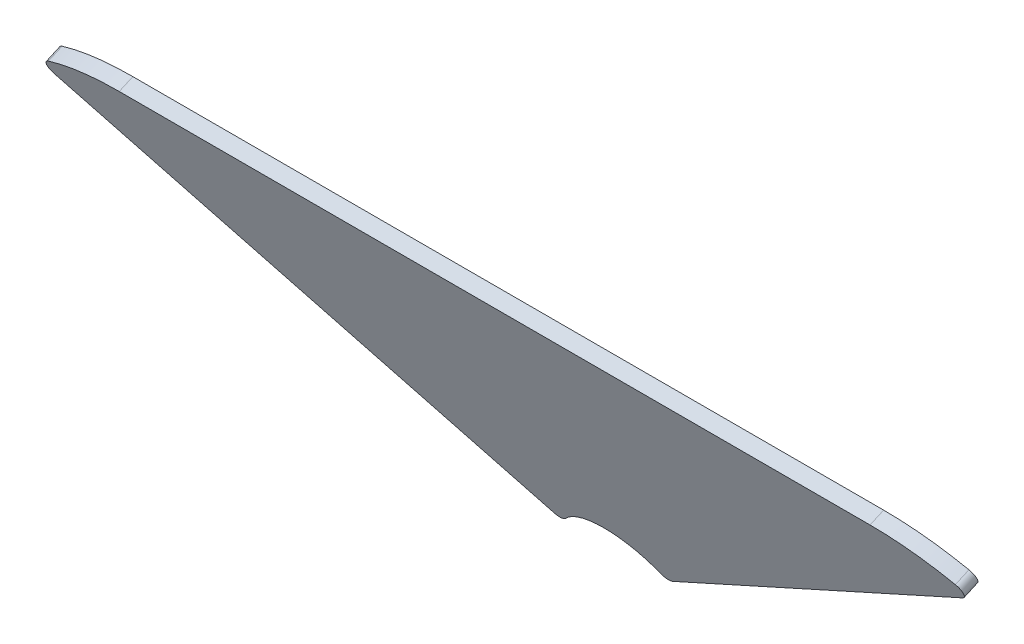
SolidWorks part; units mm, degrees
ref_plane "Front Plane" through (0, 0, 0) normal (0, 0, 1) x (1, 0, 0)
ref_plane "Top Plane" through (0, 0, 0) normal (0, 1, 0) x (1, 0, 0)
ref_plane "Right Plane" through (0, 0, 0) normal (1, 0, 0) x (0, 0, -1)
sketch "Sketch2" plane through (837.1765, 0, 0) normal (1, 0, 0) x (0, 0, -1)
  line L0 (-1722.9912, 961.5315) -> (-1717.1925, 964.1196)
  line L1 (-1717.1925, 964.1196) -> (-1664.5115, 846.0878)
  circle A1 centre (-1734.5884, 956.3553) radius 12.7 construction
  spline S3 degree 3 poles (-1672.5958, 849.9723) (-1673.5477, 849.8952) (-1674.1749, 849.8046) (-1675.1056, 849.6161) (-1675.4141, 849.5444) (-1676.0278, 849.383) (-1676.3323, 849.2934) (-1677.2211, 849.0032) (-1677.7876, 848.7801) (-1678.6002, 848.3983) (-1678.8658, 848.2625) (-1679.3759, 847.9783) (-1679.6212, 847.8297) (-1680.3284, 847.3632) (-1680.7621, 847.0248) (-1681.5498, 846.2807) (-1681.8942, 845.8836) (-1682.4751, 845.0381) (-1682.7133, 844.5881) (-1683.068, 843.6224) (-1683.1776, 843.1254) (-1683.239, 842.3556) (-1683.2421, 842.095) (-1683.212, 841.5648) (-1683.1783, 841.294) (-1683.024, 840.491) (-1682.8511, 839.9617) (-1682.4897, 839.1774) (-1682.3514, 838.9169) (-1682.0477, 838.4116) (-1681.8818, 838.1655) (-1681.523, 837.6858) (-1681.3302, 837.4523) (-1680.9182, 836.9982) (-1680.6991, 836.7779) (-1680.0161, 836.1492) (-1679.5231, 835.7681) (-1678.7294, 835.2541) (-1678.4548, 835.0921) (-1677.8968, 834.7935) (-1677.6124, 834.6562) (-1676.7433, 834.2805) (-1676.1429, 834.0779) (-1674.8968, 833.7796) (-1674.2664, 833.6881) (-1673.0044, 833.6277) (-1672.3691, 833.6585) (-1671.0981, 833.8585) (-1670.4856, 834.024) (-1669.6006, 834.3689) (-1669.3112, 834.5) (-1668.7442, 834.7954) (-1668.4663, 834.9601) (-1667.6711, 835.4907) (-1667.1844, 835.8964) (-1666.5163, 836.577) (-1666.3034, 836.8169) (-1665.9068, 837.3099) (-1665.722, 837.564) (-1665.3779, 838.0864) (-1665.2187, 838.3547) (-1664.9255, 838.9046) (-1664.791, 839.1879) (-1664.432, 840.0421) (-1664.2502, 840.6186) (-1663.9965, 841.7808) (-1663.9255, 842.3714) (-1663.9008, 843.5079) (-1663.945, 844.0593) (-1664.0977, 844.8597) (-1664.1634, 845.1221) (-1664.3209, 845.6257) (-1664.413, 845.8686) (-1664.6235, 846.3369) (-1664.7419, 846.5625) (-1665.0057, 846.9964) (-1665.1519, 847.2059) (-1665.6245, 847.798) (-1665.9841, 848.1462) (-1666.7949, 848.758) (-1667.2503, 849.0223) (-1668.2222, 849.4504) (-1668.7421, 849.6177) (-1669.5789, 849.8031) (-1669.8673, 849.8536) (-1670.4504, 849.9311) (-1670.7467, 849.9585) (-1671.3491, 849.9916) (-1671.6553, 849.9974) (-1672.278, 849.9878) (-1672.5958, 849.9723) (-1673.5477, 849.8952) (-1674.1749, 849.8046) knots -0.015625 -0.015625 0 0 0.03125 0.03125 0.046875 0.046875 0.0625 0.0625 0.09375 0.09375 0.109375 0.109375 0.125 0.125 0.15625 0.15625 0.1875 0.1875 0.21875 0.21875 0.25 0.25 0.265625 0.265625 0.28125 0.28125 0.3125 0.3125 0.328125 0.328125 0.34375 0.34375 0.359375 0.359375 0.375 0.375 0.40625 0.40625 0.421875 0.421875 0.4375 0.4375 0.46875 0.46875 0.5 0.5 0.53125 0.53125 0.5625 0.5625 0.578125 0.578125 0.59375 0.59375 0.625 0.625 0.640625 0.640625 0.65625 0.65625 0.671875 0.671875 0.6875 0.6875 0.71875 0.71875 0.75 0.75 0.78125 0.78125 0.796875 0.796875 0.8125 0.8125 0.828125 0.828125 0.84375 0.84375 0.875 0.875 0.90625 0.90625 0.9375 0.9375 0.953125 0.953125 0.96875 0.96875 0.984375 0.984375 1 1 1.03125 1.03125 1.046875 only from (-1672.9131, 849.9466) to (-1672.9131, 849.9466) construction
  point P4 (-1734.5884, 956.3553)
  dimension "D1" = 6.35
ref_plane "Plane1" through (837.1765, 964.1196, 1717.1925) normal (0, 0.4076, -0.9132) x (-1, 0, 0)
sketch "Sketch3" plane through (837.1765, 964.1196, 1717.1925) normal (0, 0.4076, -0.9132) x (-1, 0, 0)
  line L0 (200.465, -319.1426) -> (364.1746, -212.1254)
  line L1 (200.465, -319.1426) -> (364.1746, -212.1254) construction
  line L2 (348.2988, -210.3187) -> (28.1004, -210.3187)
  line L3 (348.2988, -210.3187) -> (28.1004, -210.3187) construction
  line L4 (12.2244, -212.1253) -> (175.9323, -319.1412)
  line L5 (12.2244, -212.1253) -> (175.9323, -319.1412) construction
  line L6 (166.1468, -335.4914) -> (166.1318, -335.493)
  line L7 (166.1468, -335.4914) -> (166.1318, -335.493) construction
  line L8 (166.1318, -335.493) -> (-9.0348, -220.9873)
  line L9 (166.1318, -335.493) -> (-9.0348, -220.9873) construction
  line L10 (28.1004, -184.9187) -> (348.2988, -184.9187)
  line L11 (28.1004, -184.9187) -> (348.2988, -184.9187) construction
  line L12 (385.4341, -220.9873) -> (210.2675, -335.493)
  line L13 (385.4341, -220.9873) -> (210.2675, -335.493) construction
  line L14 (210.2675, -335.493) -> (210.2565, -335.4943)
  line L15 (210.2675, -335.493) -> (210.2565, -335.4943) construction
  line L16 (-9.0348, -220.9873) -> (12.2244, -212.1253) construction
  line L17 (28.1004, -184.9187) -> (28.1004, -210.3187) construction
  line L18 (348.2988, -184.9187) -> (348.2988, -210.3187) construction
  line L19 (177.1127, -118.42) -> (187.5358, -134.3648) construction
  line L20 (143.0858, -118.42) -> (132.6627, -134.3648) construction
  line L21 (364.1746, -212.1254) -> (385.4341, -220.9873) construction
  line L22 (175.9323, -319.1412) -> (200.465, -319.1426) construction
  line L23 (137.8743, -126.3924) -> (-26.5056, -18.9376)
  line L24 (-26.5056, -18.9376) -> (-39.0764, -10.7201)
  line L25 (-39.0764, -10.7201) -> (-51.6473, -2.5025) construction
  line L26 (182.3243, -126.3924) -> (346.7039, -18.9376)
  line L27 (346.7039, -18.9376) -> (359.2746, -10.7202)
  line L28 (359.2746, -10.7202) -> (371.8453, -2.5027) construction
  line L29 (320.1984, 0) -> (0, 0)
  arc A1 (0, 0) -> (-39.0764, -10.7201) centre (0, -76.5802) ccw
  arc A2 (320.1984, 0) -> (359.2746, -10.7202) centre (320.1984, -76.5785) cw
  arc A3 (182.3243, -126.3924) -> (137.8743, -126.3924) centre (160.0993, -140.9209) ccw
  spline S0 degree 3 poles (659.9519, 743.1282) (428.1653, -254.3173) (397.4834, -218.3344) (360.2524, -211.3258) (358.2751, -211.0142) (356.2894, -210.7599) (354.2973, -210.5624) (352.3004, -210.422) (350.6337, -210.3538) (315.7098, -209.6595) (281.1145, -227.6118) (267.7262, 786.4165) knots -6.722567 -6.722567 -6.722567 -6.722567 0.125 0.25 0.375 0.5 0.625 0.75 0.875 0.9375 7.29437 7.29437 7.29437 7.29437 only from (364.1746, -212.1254) to (348.2988, -210.3187)
  spline S1 degree 3 poles (364.1746, -212.1254) (363.5233, -211.9804) (362.2195, -211.6961) (360.2524, -211.3258) (358.2751, -211.0142) (356.2894, -210.7599) (354.2973, -210.5624) (352.3004, -210.422) (350.6337, -210.3538) (349.2996, -210.3272) (348.6324, -210.3211) (348.2988, -210.3187) knots 0 0 0 0 0.125 0.25 0.375 0.5 0.625 0.75 0.875 0.9375 1 1 1 1 construction
  spline S2 degree 3 poles (97.7861, 787.2485) (97.2182, -236.2705) (60.6222, -208.9011) (24.0988, -210.4229) (22.1019, -210.5631) (20.1097, -210.7605) (18.1241, -211.0144) (16.4762, -211.2736) (15.1629, -211.5099) (14.1806, -211.7016) (13.3646, -211.8735) (-18.1256, -218.7856) (-47.5419, -233.8893) (-286.4808, 742.2125) knots -6.472941 -6.472941 -6.472941 -6.472941 0.125 0.25 0.375 0.5 0.625 0.75 0.8125 0.875 0.9375 0.96875 6.915062 6.915062 6.915062 6.915062 only from (28.1004, -210.3187) to (12.2244, -212.1253)
  spline S3 degree 3 poles (28.1004, -210.3187) (27.4332, -210.3239) (26.0988, -210.3395) (24.0988, -210.4229) (22.1019, -210.5631) (20.1097, -210.7605) (18.1241, -211.0144) (16.4762, -211.2736) (15.1629, -211.5099) (14.1806, -211.7016) (13.3646, -211.8735) (12.7129, -212.0165) (12.3872, -212.089) (12.2244, -212.1253) knots 0 0 0 0 0.125 0.25 0.375 0.5 0.625 0.75 0.8125 0.875 0.9375 0.96875 1 1 1 1 construction
  spline S4 degree 3 poles (982.7808, 271.6051) (158.1545, -326.467) (174.5052, -317.3606) (176.0525, -319.2694) (176.089, -319.3623) (176.1027, -319.4622) (176.1033, -319.564) (176.0581, -319.8426) (175.748, -320.4402) (175.1304, -321.2349) (174.4623, -322.0037) (173.9265, -322.6112) (172.5796, -324.1234) (170.345, -326.7511) (168.4081, -329.8622) (167.3716, -332.0603) (166.987, -332.9968) (166.7089, -333.7572) (166.5162, -334.3334) (166.3648, -334.8169) (165.1032, -339.4892) (157.37, -341.2292) (-739.9858, 87.4471) knots -0.369024 -0.369024 -0.369024 -0.369024 0.003906 0.007812 0.015625 0.019531 0.023438 0.03125 0.0625 0.125 0.1875 0.21875 0.25 0.5 0.75 0.8125 0.875 0.90625 0.9375 0.96875 0.984375 1.679663 1.679663 1.679663 1.679663 only from (175.9323, -319.1412) to (166.1468, -335.4914)
  spline S5 degree 3 poles (175.9323, -319.1412) (175.9519, -319.1578) (175.9897, -319.1918) (176.0525, -319.2694) (176.089, -319.3623) (176.1027, -319.4622) (176.1033, -319.564) (176.0581, -319.8426) (175.748, -320.4402) (175.1304, -321.2349) (174.4623, -322.0037) (173.9265, -322.6112) (172.5796, -324.1234) (170.345, -326.7511) (168.4081, -329.8622) (167.3716, -332.0603) (166.987, -332.9968) (166.7089, -333.7572) (166.5162, -334.3334) (166.3648, -334.8169) (166.2586, -335.2104) (166.1929, -335.4018) (166.1468, -335.4914) knots 0 0 0 0 0.003906 0.007812 0.015625 0.019531 0.023438 0.03125 0.0625 0.125 0.1875 0.21875 0.25 0.5 0.75 0.8125 0.875 0.90625 0.9375 0.96875 0.984375 1 1 1 1 construction
  spline S6 degree 3 poles (-493.6996, 653.7081) (83.9817, -212.3541) (22.0311, -198.2847) (-13.0482, -223.7444) (-14.3371, -224.7316) (-15.601, -225.7507) (-17.2514, -227.1514) (-19.2467, -228.98) (-21.5249, -231.2949) (-24.3974, -234.5355) (-27.66, -238.8621) (-30.436, -243.5165) (-32.339, -247.4067) (-33.6013, -250.3996) (-34.6934, -253.4586) (-35.4578, -256.0552) (-35.9789, -258.1561) (-36.3229, -259.7426) (-42.747, -294.5132) (-19.81, -333.8714) (-1033.9267, -186.5236) knots -2.378042 -2.378042 -2.378042 -2.378042 0.0625 0.09375 0.125 0.15625 0.1875 0.25 0.3125 0.375 0.5 0.625 0.6875 0.75 0.8125 0.875 0.90625 0.9375 0.96875 2.948348 2.948348 2.948348 2.948348 only from (-9.0348, -220.9873) to (-36.8675, -262.943)
  spline S7 degree 3 poles (-9.0348, -220.9873) (-9.9432, -221.5758) (-11.2964, -222.473) (-13.0482, -223.7444) (-14.3371, -224.7316) (-15.601, -225.7507) (-17.2514, -227.1514) (-19.2467, -228.98) (-21.5249, -231.2949) (-24.3974, -234.5355) (-27.66, -238.8621) (-30.436, -243.5165) (-32.339, -247.4067) (-33.6013, -250.3996) (-34.6934, -253.4586) (-35.4578, -256.0552) (-35.9789, -258.1561) (-36.3229, -259.7426) (-36.6178, -261.3389) (-36.7862, -262.408) (-36.8675, -262.943) knots 0 0 0 0 0.0625 0.09375 0.125 0.15625 0.1875 0.25 0.3125 0.375 0.5 0.625 0.6875 0.75 0.8125 0.875 0.90625 0.9375 0.96875 1 1 1 1 construction
  spline S8 degree 3 poles (-47.8786, -256.9695) (-36.9078, -258.8257) (-2.6541, -272.3181) (-50.068, -265.5733) (-97.5183, -258.8233) (-60.8226, -255.4226) (-49.7712, -256.7002) knots -1.046927 -1.046927 -1.046927 -1.046927 0.5 0.5 0.5 2.047388 2.047388 2.047388 2.047388 weights 4.840134 1.66871 0.388666 1 0.388483 1.669474 4.842974 only from (-36.8675, -262.943) to (-62.0131, -259.366)
  spline S9 degree 3 poles (-36.8675, -262.943) (-37.1611, -265.5366) (-42.6448, -266.6293) (-50.068, -265.5733) (-57.4912, -264.5173) (-62.4534, -261.9387) (-62.0131, -259.366) knots 0 0 0 0 0.5 0.5 0.5 1 1 1 1 weights 1 0.802404 0.802404 1 0.802404 0.802404 1 construction
  spline S10 degree 3 poles (-1060.3982, -202.94) (-56.4438, -329.2134) (-67.2811, -292.1623) (-61.6548, -257.0711) (-61.3619, -255.4381) (-60.9617, -253.4879) (-60.0654, -249.6084) (-57.6106, -241.3303) (-49.7965, -224.3685) (-35.6466, -208.0634) (-17.9273, -196.2171) (-5.752, -190.8135) (4.4288, -187.7666) (12.2284, -186.1252) (18.8192, -185.3063) (73.9472, -181.7994) (128.2452, -228.2224) (116.8317, 811.1153) knots -0.805545 -0.805545 -0.805545 -0.805545 0.007812 0.015625 0.03125 0.046875 0.0625 0.125 0.25 0.5 0.625 0.75 0.8125 0.875 0.9375 0.96875 2.175289 2.175289 2.175289 2.175289 only from (-62.0131, -259.366) to (28.1004, -184.9187)
  spline S11 degree 3 poles (-62.0131, -259.366) (-61.9641, -259.0378) (-61.865, -258.3816) (-61.6548, -257.0711) (-61.3619, -255.4381) (-60.9617, -253.4879) (-60.0654, -249.6084) (-57.6106, -241.3303) (-49.7965, -224.3685) (-35.6466, -208.0634) (-17.9273, -196.2171) (-5.752, -190.8135) (4.4288, -187.7666) (12.2284, -186.1252) (18.8192, -185.3063) (24.1188, -184.9692) (26.7732, -184.9275) (28.1004, -184.9187) knots 0 0 0 0 0.007812 0.015625 0.03125 0.046875 0.0625 0.125 0.25 0.5 0.625 0.75 0.8125 0.875 0.9375 0.96875 1 1 1 1 construction
  spline S12 degree 3 poles (929.1577, -998.9148) (26.9808, -381.5261) (268.5777, -127.2907) (408.505, -203.9885) (426.1982, -224.3663) (434.0103, -241.3309) (436.4648, -249.6066) (437.3606, -253.4879) (437.7608, -255.4383) (438.0537, -257.0712) (443.7072, -292.3117) (433.0852, -329.5148) (1436.622, -201.5799) knots -2.951338 -2.951338 -2.951338 -2.951338 0.25 0.5 0.75 0.875 0.9375 0.953125 0.96875 0.984375 0.992188 1.809139 1.809139 1.809139 1.809139 only from (348.2988, -184.9187) to (438.4123, -259.366)
  spline S13 degree 3 poles (348.2988, -184.9187) (358.9172, -184.9233) (380.1516, -188.4473) (408.505, -203.9885) (426.1982, -224.3663) (434.0103, -241.3309) (436.4648, -249.6066) (437.3606, -253.4879) (437.7608, -255.4383) (438.0537, -257.0712) (438.2639, -258.3817) (438.3632, -259.0378) (438.4123, -259.366) knots 0 0 0 0 0.25 0.5 0.75 0.875 0.9375 0.953125 0.96875 0.984375 0.992188 1 1 1 1 construction
  spline S14 degree 3 poles (429.3298, -256.4787) (440.8837, -256.216) (453.9089, -261.6696) (426.4673, -265.5733) (399.0344, -269.4757) (410.0144, -260.6083) (421.1832, -257.6379) knots -0.70583 -0.70583 -0.70583 -0.70583 0.5 0.5 0.5 1.705627 1.705627 1.705627 1.705627 weights 3.01812 1.196171 0.523464 1 0.523545 1.195944 3.017197 only from (438.4123, -259.366) to (413.2667, -262.943)
  spline S15 degree 3 poles (438.4123, -259.366) (438.8526, -261.9387) (433.8904, -264.5173) (426.4673, -265.5733) (419.0441, -266.6293) (413.5604, -265.5366) (413.2667, -262.943) knots 0 0 0 0 0.5 0.5 0.5 1 1 1 1 weights 1 0.802404 0.802404 1 0.802404 0.802404 1 construction
  spline S16 degree 3 poles (1410.455, -188.0131) (395.1635, -336.6809) (419.3711, -295.7703) (412.6239, -259.2105) (412.0098, -256.5745) (411.092, -253.4587) (408.9087, -247.34) (405.3648, -240.5921) (400.144, -233.6703) (396.4438, -229.712) (393.2517, -226.7855) (390.7497, -224.7145) (353.7782, -197.1496) (288.4588, -212.0584) (872.3304, 652.4537) knots -2.022142 -2.022142 -2.022142 -2.022142 0.03125 0.0625 0.125 0.1875 0.25 0.5 0.625 0.75 0.8125 0.875 0.9375 3.474833 3.474833 3.474833 3.474833 only from (413.2667, -262.943) to (385.4341, -220.9873)
  spline S17 degree 3 poles (413.2667, -262.943) (413.1855, -262.408) (413.0167, -261.3389) (412.6239, -259.2105) (412.0098, -256.5745) (411.092, -253.4587) (408.9087, -247.34) (405.3648, -240.5921) (400.144, -233.6703) (396.4438, -229.712) (393.2517, -226.7855) (390.7497, -224.7145) (388.146, -222.7732) (386.3426, -221.5756) (385.4341, -220.9873) knots 0 0 0 0 0.03125 0.0625 0.125 0.1875 0.25 0.5 0.625 0.75 0.8125 0.875 0.9375 1 1 1 1 construction
  spline S18 degree 3 poles (1000.6787, 277.0647) (258.2318, -323.4154) (211.9671, -341.0766) (210.1437, -335.2146) (210.0999, -335.0684) (210.0561, -334.9224) (209.9827, -334.6795) (209.8633, -334.292) (209.6891, -333.7631) (209.4829, -333.1919) (209.261, -332.6267) (208.945, -331.8812) (208.3413, -330.5985) (207.5457, -329.1845) (206.6638, -327.8234) (205.9639, -326.8282) (205.2304, -325.857) (204.4683, -324.9081) (203.8136, -324.1339) (203.2815, -323.5219) (202.745, -322.9138) (202.2044, -322.3095) (201.6701, -321.6994) (201.3429, -321.3124) (201.0889, -320.9963) (200.9039, -320.7549) (200.7268, -320.5075) (200.5614, -320.2517) (200.4403, -320.0277) (200.3608, -319.8391) (200.3156, -319.6924) (200.2921, -319.5407) (200.2998, -319.414) (200.3287, -319.3195) (200.363, -319.254) (201.9646, -317.2491) (217.5274, -324.4122) (-635.2893, 229.8776) knots -0.918902 -0.918902 -0.918902 -0.918902 0.007812 0.015625 0.023438 0.03125 0.039062 0.0625 0.09375 0.125 0.15625 0.1875 0.25 0.375 0.4375 0.5 0.5625 0.625 0.6875 0.71875 0.75 0.8125 0.84375 0.875 0.890625 0.90625 0.921875 0.9375 0.953125 0.960938 0.96875 0.976562 0.984375 0.988281 0.992188 0.996094 1.390011 1.390011 1.390011 1.390011 only from (210.2565, -335.4943) to (200.465, -319.1426)
  spline S19 degree 3 poles (210.2565, -335.4943) (210.2317, -335.451) (210.189, -335.3604) (210.1437, -335.2146) (210.0999, -335.0684) (210.0561, -334.9224) (209.9827, -334.6795) (209.8633, -334.292) (209.6891, -333.7631) (209.4829, -333.1919) (209.261, -332.6267) (208.945, -331.8812) (208.3413, -330.5985) (207.5457, -329.1845) (206.6638, -327.8234) (205.9639, -326.8282) (205.2304, -325.857) (204.4683, -324.9081) (203.8136, -324.1339) (203.2815, -323.5219) (202.745, -322.9138) (202.2044, -322.3095) (201.6701, -321.6994) (201.3429, -321.3124) (201.0889, -320.9963) (200.9039, -320.7549) (200.7268, -320.5075) (200.5614, -320.2517) (200.4403, -320.0277) (200.3608, -319.8391) (200.3156, -319.6924) (200.2921, -319.5407) (200.2998, -319.414) (200.3287, -319.3195) (200.363, -319.254) (200.4097, -319.1955) (200.4462, -319.16) (200.465, -319.1426) knots 0 0 0 0 0.007812 0.015625 0.023438 0.03125 0.039062 0.0625 0.09375 0.125 0.15625 0.1875 0.25 0.375 0.4375 0.5 0.5625 0.625 0.6875 0.71875 0.75 0.8125 0.84375 0.875 0.890625 0.90625 0.921875 0.9375 0.953125 0.960938 0.96875 0.976562 0.984375 0.988281 0.992188 0.996094 1 1 1 1 construction
  point P22 (0, 0)
  point P23 (-26.5056, -18.9376)
  point P25 (137.8743, -126.3924)
  point P26 (320.1984, 0)
  point P27 (346.7037, -18.9376)
  point P28 (182.3243, -126.3924)
  point P31 (188.1987, -319.1419)
  point P32 (188.1987, -319.1419)
  dimension "D1" = 44.45
extrude "Boss-Extrude1" add sketch "Sketch3" along normal blind 6.35
fillet "Fillet1" radius 3.81 4 edges at (699.3022, 849.9957, 1662.7788) (654.8522, 849.9957, 1662.7789) (477.9018, 955.6243, 1709.9239) (876.2529, 955.6244, 1709.924)
